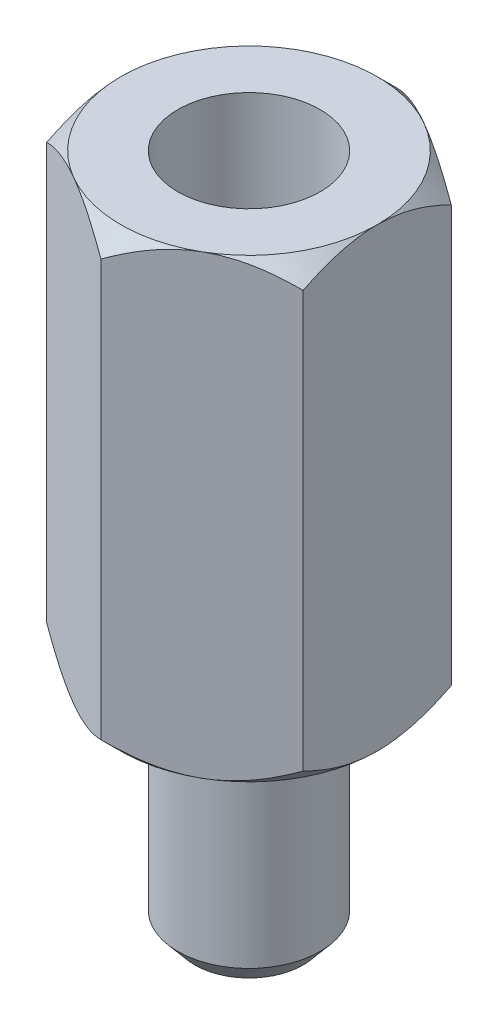
SolidWorks part; units mm, degrees
ref_plane "Front Plane" through (0, 0, 0) normal (0, 0, 1) x (1, 0, 0)
ref_plane "Top Plane" through (0, 0, 0) normal (0, 1, 0) x (1, 0, 0)
ref_plane "Right Plane" through (0, 0, 0) normal (1, 0, 0) x (0, 0, -1)
sketch "Sketch1" plane through (0, 0, 0) normal (0, 1, 0) x (1, 0, 0)
  circle A0 centre (0, 0) radius 1.25
  dimension "D1" = 2.5
extrude "Boss-Extrude1" add sketch "Sketch1" along normal blind 3.9
sketch "Sketch2" plane through (0, 3.9, 0) normal (0, 1, 0) x (1, 0, 0)
  line L1 (0, 2.5981) -> (-2.25, 1.299)
  line L2 (-2.25, 1.299) -> (-2.25, -1.299)
  line L3 (-2.25, -1.299) -> (0, -2.5981)
  line L4 (0, -2.5981) -> (2.25, -1.299)
  line L5 (2.25, -1.299) -> (2.25, 1.299)
  line L6 (2.25, 1.299) -> (0, 2.5981)
  circle A0 centre (0, 0) radius 2.25 construction
  dimension "D1" = 4.5
extrude "Boss-Extrude2" add sketch "Sketch2" along normal blind 8
sketch "Sketch3" plane through (0, 11.9, 0) normal (0, 1, 0) x (1, 0, 0)
  circle A0 centre (0, 0) radius 1.25
  dimension "D1" = 2.5
extrude "Cut-Extrude1" cut sketch "Sketch3" against normal blind 4.8
sketch "Sketch4" plane through (0, 11.9, 0) normal (0, 1, 0) x (1, 0, 0)
  circle A0 centre (0, 0) radius 2.25
extrude "Cut-Extrude3" cut sketch "Sketch4" against normal through all draft 45 flip side to cut
sketch "Sketch6" plane through (0, 3.9, 0) normal (0, -1, 0) x (1, 0, 0)
  circle A0 centre (0, 0) radius 2.25
extrude "Cut-Extrude4" cut sketch "Sketch6" against normal through all draft 45 flip side to cut
chamfer "Chamfer1" distance 0.3 angle 50 1 edges at (0, 0, 1.25)
